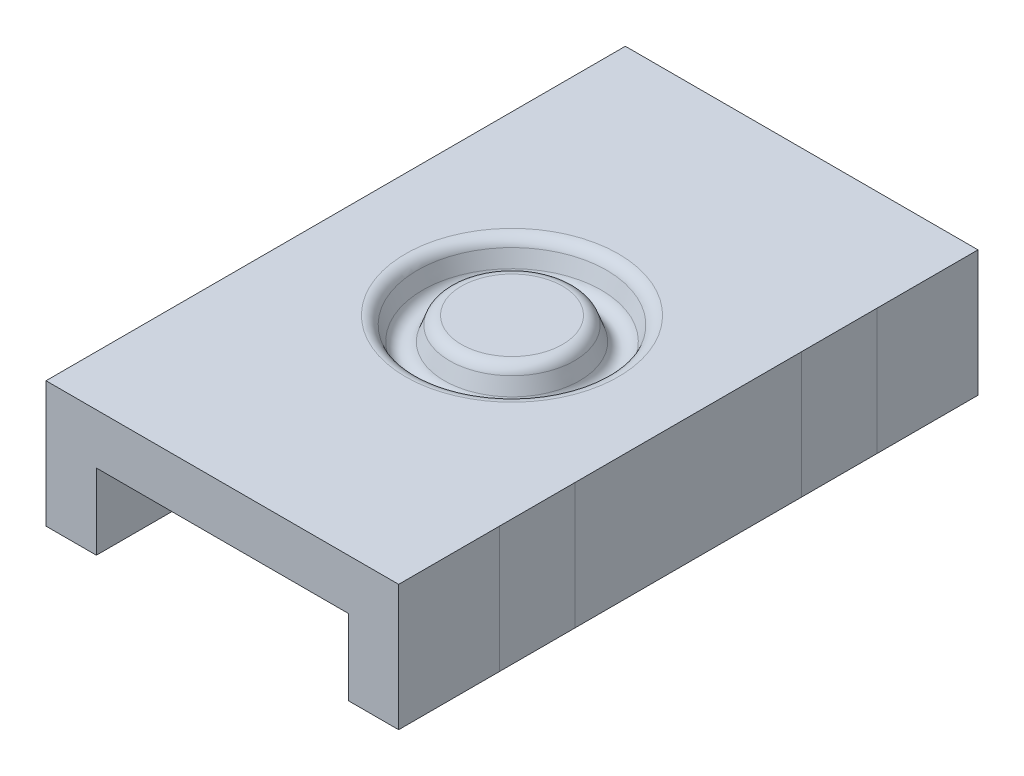
SolidWorks part; units mm, degrees
ref_plane "Front Plane" through (0, 0, 0) normal (0, 0, 1) x (1, 0, 0)
ref_plane "Top Plane" through (0, 0, 0) normal (0, 1, 0) x (1, 0, 0)
ref_plane "Right Plane" through (0, 0, 0) normal (1, 0, 0) x (0, 0, -1)
sketch "Sketch1" plane through (0, 0, 0) normal (0, 1, 0) x (1, 0, 0)
  line L0 (-14, 23) -> (14, -23) construction
  line L1 (-14, -23) -> (14, -23)
  line L2 (-14, -23) -> (-14, 23)
  line L3 (-14, 23) -> (14, 23)
  line L4 (14, -23) -> (14, 23)
  point P4 (0, 0)
  dimension "D1" = 46
  dimension "D2" = 28
extrude "Boss-Extrude1" add sketch "Sketch1" along normal blind 10
sketch "Sketch2" plane through (0, 0, 23) normal (0, 0, 1) x (1, 0, 0)
  line L0 (-14, 0) -> (14, 0) construction
  line L1 (-10, 0) -> (10, 0)
  line L2 (-10, 0) -> (-10, 6)
  line L3 (-10, 6) -> (10, 6)
  line L4 (10, 0) -> (10, 6)
  line L5 (-14, 10) -> (-14, 0) construction
  point P6 (0, 0)
  dimension "D1" = 6
  dimension "D2" = 4
extrude "Cut-Extrude1" cut sketch "Sketch2" against normal through all
sketch "Sketch3" plane through (0, 0, 0) normal (0, 0, 1) x (1, 0, 0)
  line L0 (0, -1000.118) -> (0, 48999.882) construction
  line L1 (5.3752, 8.1871) -> (4.7153, 10)
  line L2 (-14, 10) -> (14, 10) construction
  line L3 (7.0948, 8.1871) -> (7.7547, 10)
  line L4 (7.7547, 10) -> (4.7153, 10)
  arc A0 (5.3752, 8.1871) -> (7.0948, 8.1871) centre (6.235, 8.5) ccw
  dimension "D1" = 1.83
  dimension "D2" = 12.47
  dimension "D3" = 1.5
  dimension "D4" = 20
revolve "Cut-Revolve1" cut sketch "Sketch3" angle 360 about L0
fillet "Fillet3" radius 1 2 edges at (0, 10, -4.7153) (0, 10, -7.7547)
sketch "Sketch4" plane through (14, 0, 0) normal (1, 0, 0) x (0, 0, -1)
  line L0 (-23, 10) -> (23, 10) construction
  line L1 (-15, 10) -> (-9, 10)
  line L2 (-15, 10) -> (-15, 0)
  line L3 (-15, 0) -> (-9, 0)
  line L4 (-9, 10) -> (-9, 0)
  line L5 (-23, 0) -> (23, 0) construction
  line L6 (9, 10) -> (-9, 10) construction
  line L7 (9, 10) -> (15, 10)
  line L8 (9, 10) -> (9, 0)
  line L9 (9, 0) -> (15, 0)
  line L10 (15, 10) -> (15, 0)
  point P12 (0, 10)
  dimension "D1" = 6
  dimension "D2" = 18
split line "Split Line1"
